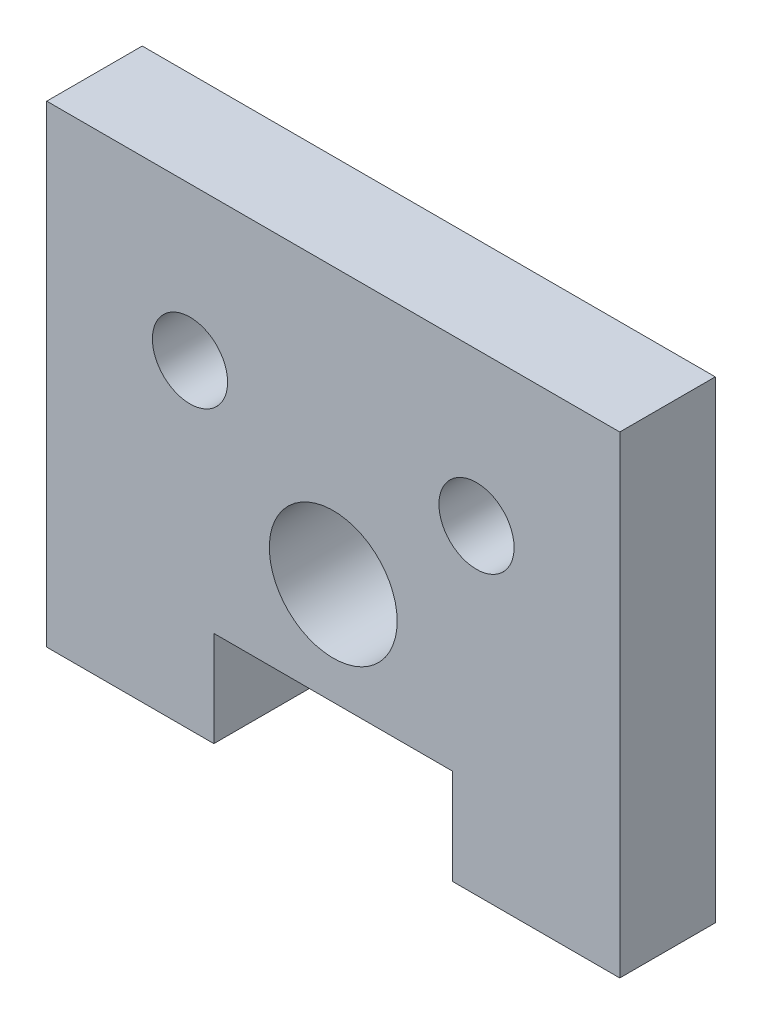
SolidWorks part; units mm, degrees
material "Acrylic (Medium-high impact)"
ref_plane "Front Plane" through (0, 0, 0) normal (0, 0, 1) x (1, 0, 0)
ref_plane "Top Plane" through (0, 0, 0) normal (0, 1, 0) x (1, 0, 0)
ref_plane "Right Plane" through (0, 0, 0) normal (1, 0, 0) x (0, 0, -1)
sketch "Sketch1" plane through (0, 0, 0) normal (0, 0, 1) x (1, 0, 0)
  line L0 (-15.875, -34.544) -> (-15.875, -21.844)
  line L1 (38.1, -34.544) -> (15.875, -34.544)
  line L2 (38.1, -34.544) -> (38.1, 34.544)
  line L4 (-38.1, -34.544) -> (-38.1, 34.544)
  line L5 (-15.875, -21.844) -> (15.875, -21.844)
  line L6 (15.875, -21.844) -> (15.875, -34.544)
  line L7 (-15.875, -34.544) -> (-38.1, -34.544)
  line L8 (0, -21.844) -> (0, -16.764)
  line L9 (-19.05, 28.3364) -> (-38.1, 28.3364)
  line L10 (-19.05, 28.3364) -> (38.1, 28.3364)
  circle A3 centre (0, -8.264) radius 8.5
  circle A4 centre (-19.05, 7.992) radius 5
  circle A5 centre (19.05, 7.992) radius 5
  point P0 (0, 0)
  point P6 (-38.1, 0)
  point P18 (0, -21.844)
  dimension "D3" = 17
  dimension "D5" = 10
  dimension "D8" = 31.75
  dimension "D9" = 12.7
  dimension "D10" = 5.08
  dimension "D4" = 16.256
  dimension "D6" = 19.05
  dimension "D7" = 19.05
  dimension "D2" = 76.2
extrude "Boss-Extrude1" add sketch "Sketch1" along normal blind 12.7
equation "\"D7@Sketch1\"=\"D6@Sketch1\""
